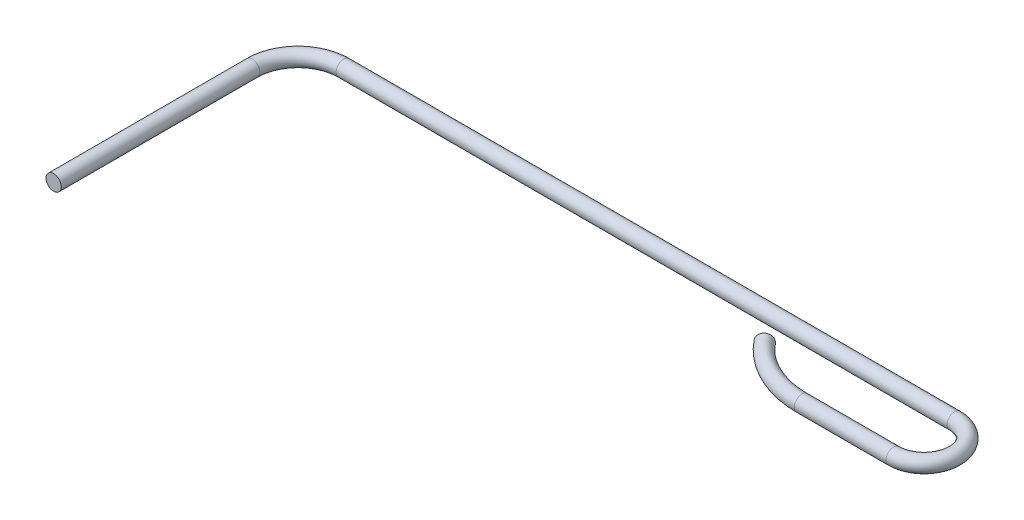
SolidWorks part; units mm, degrees
material "Cast Alloy Steel"
ref_plane "Front Plane" through (0, 0, 0) normal (0, 0, 1) x (1, 0, 0)
ref_plane "Top Plane" through (0, 0, 0) normal (0, 1, 0) x (1, 0, 0)
ref_plane "Right Plane" through (0, 0, 0) normal (1, 0, 0) x (0, 0, -1)
sketch "Sketch1" plane through (0, 0, 0) normal (0, 1, 0) x (1, 0, 0)
  line L0 (0, 0) -> (0, 65)
  line L1 (15, 80) -> (215, 80)
  line L2 (215, 60) -> (185, 60)
  arc A0 (215, 80) -> (215, 60) centre (215, 70) cw
  arc A1 (185, 60) -> (161.6161, 71.2066) centre (185, 90) cw
  arc A2 (15, 80) -> (0, 65) centre (15, 65) ccw
  point P11 (158.0588, 62.9114)
  dimension "D1" = 15
  dimension "D3" = 10
  dimension "D6" = 30
  dimension "D2" = 200
  dimension "D4" = 30
  dimension "D5" = 65
sketch "Sketch2" plane through (0, 0, 0) normal (0, 0, 1) x (1, 0, 0)
  circle A0 centre (0, 0) radius 2.5
  dimension "D1" = 5
sweep "Sweep1" add profiles "Sketch2" path "Sketch1"
other "Bounding Box"
ref_plane "Default Plane" through (-22.2653, 2.5, -73.0458) normal (0.2612, 0, 0.9653) x (0.9653, 0, -0.2612)
